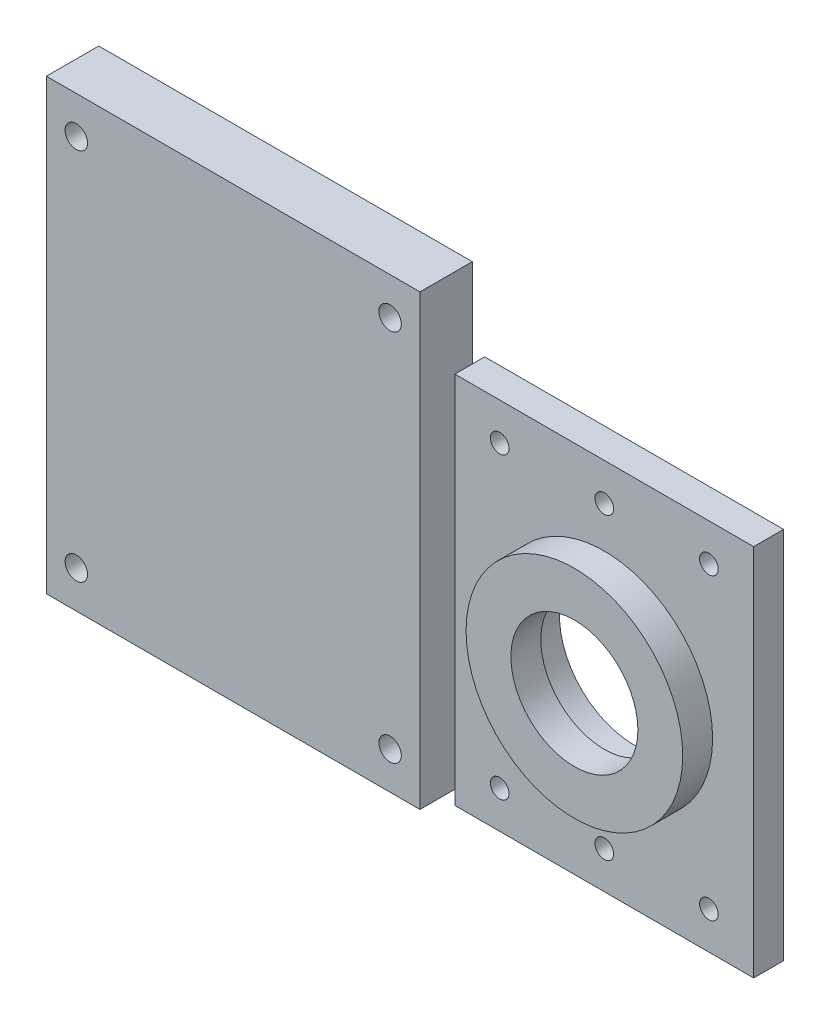
SolidWorks part; units mm, degrees
ref_plane "Front Plane" through (0, 0, 0) normal (1, 0, 0) x (0, 1, 0)
ref_plane "Top Plane" through (0, 0, 0) normal (0, 0, 1) x (0, 1, 0)
ref_plane "Right Plane" through (0, 0, 0) normal (0, 1, 0) x (-1, 0, 0)
sketch "Sketch1" plane through (0, 0, 0) normal (0, 0, 1) x (0, 1, 0)
  line L1 (-25, 20) -> (25, 20)
  line L2 (-25, 20) -> (-25, -20)
  line L3 (-25, -20) -> (25, -20)
  line L4 (25, 20) -> (25, -20)
  circle A0 centre (0, 0) radius 10
  circle A1 centre (-20, 14) radius 1.25
  circle A2 centre (-20, -14) radius 1.25
  circle A3 centre (20, 14) radius 1.25
  circle A4 centre (20, -14) radius 1.25
  circle A5 centre (-20, 0) radius 1.25
  circle A6 centre (20, 0) radius 1.25
  dimension "D1" = 20
  dimension "D6" = 2.5
  dimension "D2" = 25
  dimension "D3" = 50
  dimension "D4" = 20
  dimension "D5" = 40
  dimension "D7" = 6
  dimension "D8" = 6
  dimension "D9" = 6
  dimension "D10" = 6
  dimension "D11" = 20
  dimension "D12" = 20
  dimension "D13" = 5
  dimension "D14" = 5
  dimension "D15" = 5
  dimension "D16" = 5
  dimension "D17" = 5
  dimension "D18" = 5
extrude "Boss-Extrude1" add sketch "Sketch1" along normal blind 4
sketch "Sketch2" plane through (0, 0, 4) normal (0, 0, 1) x (1, 0, 0)
  circle A1 centre (0, 0) radius 8.5
  circle A2 centre (0, 0) radius 14.5
extrude "Boss-Extrude2" add sketch "Sketch2" along normal blind 4
sketch "Sketch3" plane through (0, 0, 0) normal (0, 0, -1) x (1, 0, 0)
  line L0 (-71.6694, -5.1991) -> (-21.6694, -5.1991) construction
  line L1 (-71.6694, 24.8009) -> (-21.6694, 24.8009)
  line L2 (-71.6694, 24.8009) -> (-71.6694, -35.1991)
  line L3 (-71.6694, -35.1991) -> (-21.6694, -35.1991)
  line L4 (-21.6694, 24.8009) -> (-21.6694, -35.1991)
  line L5 (-46.6694, 24.8009) -> (-46.6694, -8.76) construction
  circle A0 centre (-67.6694, 19.8009) radius 1.5
  circle A2 centre (-25.6694, 19.8009) radius 1.5
  circle A3 centre (-25.6694, -30.1991) radius 1.5
  circle A4 centre (-67.6694, -30.1991) radius 1.5
  dimension "D4" = 3
  dimension "D1" = 60
  dimension "D2" = 50
  dimension "D3" = 5
  dimension "D5" = 4
extrude "Boss-Extrude3" add sketch "Sketch3" against normal blind 7 separate body
